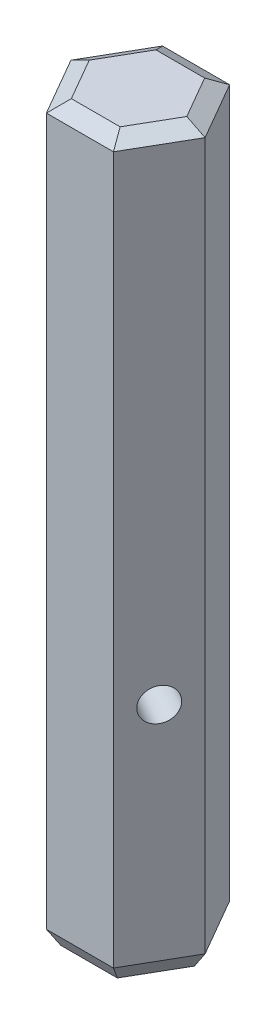
SolidWorks part; units mm, degrees
ref_plane "Přední rovina" through (0, 0, 0) normal (0, 0, 1) x (1, 0, 0)
ref_plane "Horní rovina" through (0, 0, 0) normal (0, 1, 0) x (1, 0, 0)
ref_plane "Pravá rovina" through (0, 0, 0) normal (1, 0, 0) x (0, 0, -1)
sketch "Skica1" plane through (0, 0, 0) normal (0, 1, 0) x (1, 0, 0)
  line L1 (3.6662, 0) -> (1.8331, 3.175)
  line L2 (1.8331, 3.175) -> (-1.8331, 3.175)
  line L3 (-1.8331, 3.175) -> (-3.6662, 0)
  line L4 (-3.6662, 0) -> (-1.8331, -3.175)
  line L5 (-1.8331, -3.175) -> (1.8331, -3.175)
  line L6 (1.8331, -3.175) -> (3.6662, 0)
  circle A0 centre (0, 0) radius 3.175 construction
  dimension "D1" = 6.35
extrude "Přidat vysunutím1" add sketch "Skica1" along normal blind 40
chamfer "Zkosení1" distance 0.5 angle 60 12 edges at (0, 40, 3.175) (-2.7496, 40, 1.5875) (-2.7496, 40, -1.5875) (0, 40, -3.175) (2.7496, 40, -1.5875) (2.7496, 40, 1.5875) (2.7496, 0, -1.5875) (0, 0, -3.175) (-2.7496, 0, -1.5875) (-2.7496, 0, 1.5875) (0, 0, 3.175) (2.7496, 0, 1.5875)
sketch "Skica2" plane through (2.7496, 0, 1.5875) normal (0.866, 0, 0.5) x (0.5, 0, -0.866)
  line L0 (3.0888, 0) -> (1.5444, 0) construction
  circle A0 centre (0, 13) radius 0.9
  point P4 (0, 0)
  dimension "D1" = 1.8
  dimension "D2" = 13
extrude "Odebrat vysunutím1" cut sketch "Skica2" against normal through all
